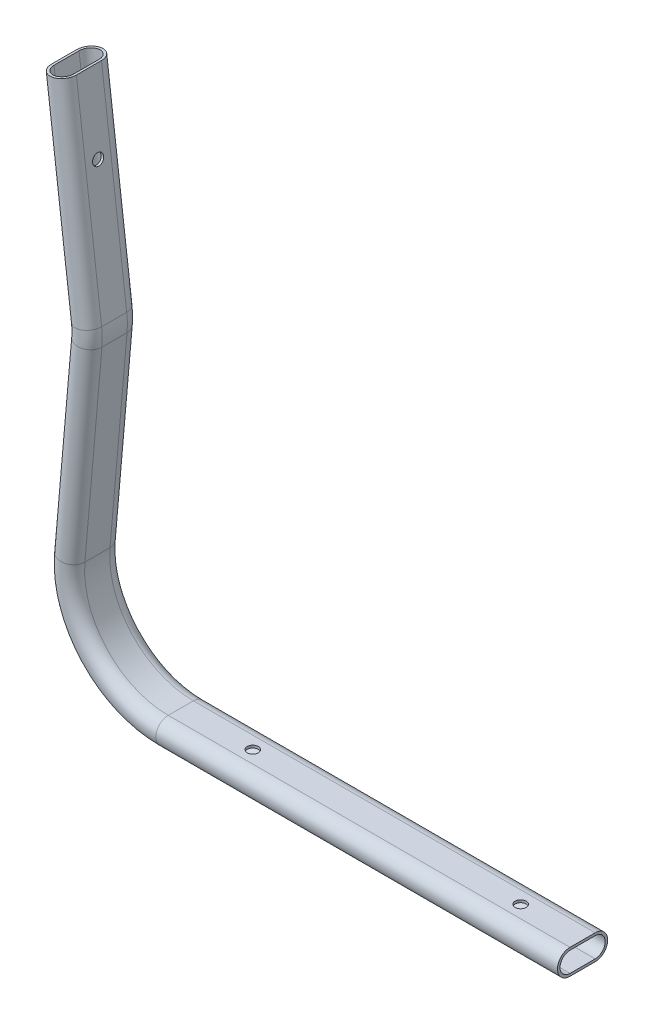
SolidWorks part; units mm, degrees
material "Простая углеродистая сталь"
ref_plane "Спереди" through (0, 0, 0) normal (0, 0, 1) x (1, 0, 0)
ref_plane "Сверху" through (0, 0, 0) normal (0, 1, 0) x (1, 0, 0)
ref_plane "Справа" through (0, 0, 0) normal (1, 0, 0) x (0, 0, -1)
sketch "Эскиз1" plane through (0, 0, 0) normal (0, 0, 1) x (1, 0, 0)
  line L0 (0, 0) -> (-240, 0)
  line L1 (-304.7527, 70.6651) -> (-294.5791, 186.9495)
  line L2 (-294.7068, 194.2654) -> (-309.7767, 317)
  arc A0 (-304.7527, 70.6651) -> (-240, 0) centre (-240, 65) ccw
  arc A1 (-294.5791, 186.9495) -> (-294.7068, 194.2654) centre (-329.4459, 190) ccw
  dimension "D1" = 65
  dimension "D4" = 35
  dimension "D2" = 240
  dimension "D3" = 85
  dimension "D5" = 190
  dimension "D6" = 168
  dimension "D7" = 317
sketch "Эскиз2" plane through (0, 0, 0) normal (1, 0, 0) x (0, 0, -1)
  line L0 (-7.5, 7.5) -> (7.5, 7.5) construction
  line L1 (-7.5, 15) -> (7.5, 15)
  line L2 (-7.5, 0) -> (7.5, 0)
  line L3 (-7.5, 13.5) -> (7.5, 13.5)
  line L4 (-7.5, 1.5) -> (7.5, 1.5)
  arc A0 (-7.5, 15) -> (-7.5, 0) centre (-7.5, 7.5) ccw
  arc A1 (7.5, 0) -> (7.5, 15) centre (7.5, 7.5) ccw
  arc A2 (7.5, 1.5) -> (7.5, 13.5) centre (7.5, 7.5) ccw
  arc A3 (-7.5, 13.5) -> (-7.5, 1.5) centre (-7.5, 7.5) ccw
  point P2 (0, 7.5)
  dimension "D1" = 15
  dimension "D2" = 30
  dimension "D3" = 1.5
sweep "По траектории1" add profiles "Эскиз2" path "Эскиз1"
sketch "Эскиз3" plane through (0, 15, 0) normal (0, 1, 0) x (1, 0, 0)
  line L0 (0, 0) -> (-37, 0) construction
  line L1 (0, 7.5) -> (0, -7.5) construction
  line L2 (-37, 0) -> (-197, 0) construction
  circle A0 centre (-197, 0) radius 3.3
  circle A1 centre (-37, 0) radius 3.3
  dimension "D3" = 6.6
  dimension "D1" = 37
  dimension "D2" = 160
extrude "Вырез-Вытянуть1" cut sketch "Эскиз3" against normal through all
sketch "Эскиз4" plane through (-251.943, -30.9347, 0) normal (0.9925, 0.1219, 0) x (0, 0, -1)
  line L0 (0, 352.3894) -> (0, 307.3894) construction
  line L1 (7.5, 352.3894) -> (-7.5, 352.3894) construction
  circle A0 centre (0, 307.3894) radius 3.3
  dimension "D1" = 6.6
  dimension "D2" = 45
extrude "Вырез-Вытянуть2" cut sketch "Эскиз4" against normal through all
